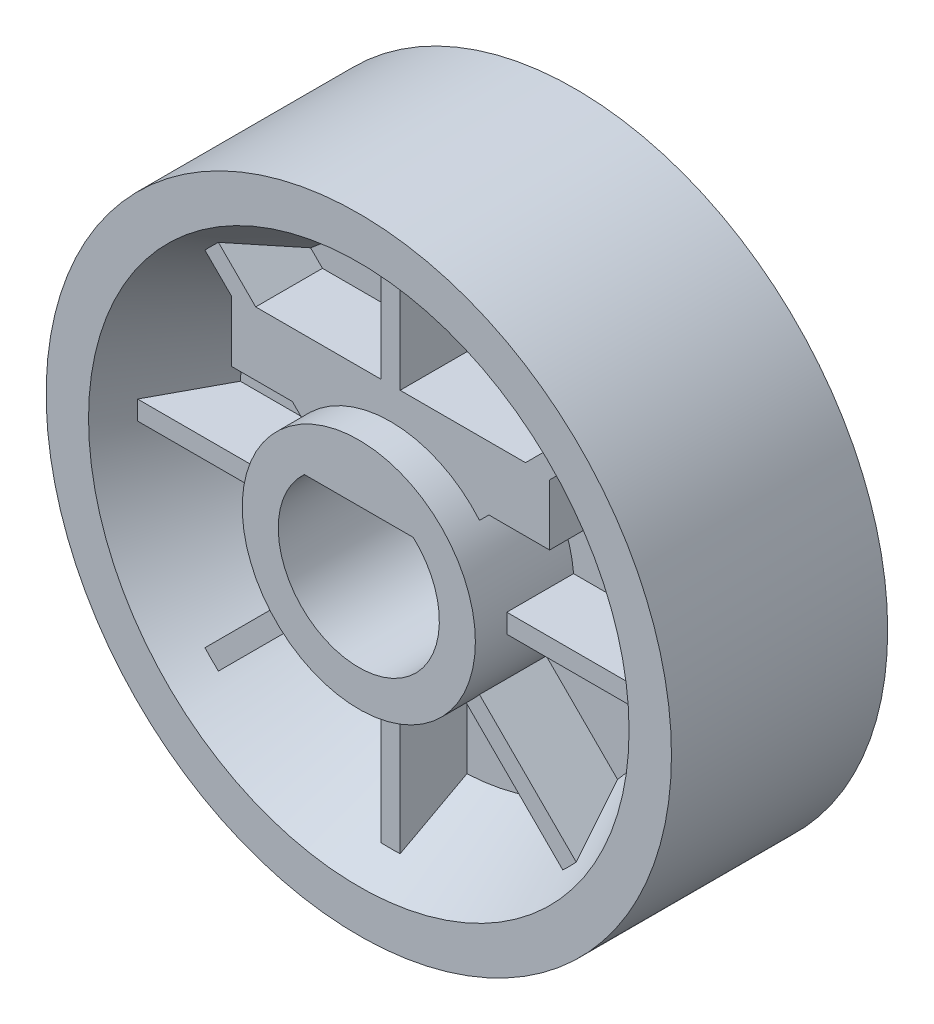
SolidWorks part; units mm, degrees
material "ABS"
ref_plane "Спереди" through (0, 0, 0) normal (0, 0, 1) x (1, 0, 0)
ref_plane "Сверху" through (0, 0, 0) normal (0, 1, 0) x (1, 0, 0)
ref_plane "Справа" through (0, 0, 0) normal (1, 0, 0) x (0, 0, -1)
sketch "Эскиз1" plane through (0, 0, 0) normal (0, 1, 0) x (1, 0, 0)
  line L0 (0, 0) -> (0, 15.044) construction
  line L1 (0, 0) -> (-5, 0) construction
  line L2 (-5, 0) -> (-11, 0)
  line L3 (-11, 0) -> (-11, 9.3)
  line L4 (-11, 9.3) -> (-20.5, 9.3)
  line L5 (-20.5, 9.3) -> (-25.5, 0)
  line L6 (-25.5, 0) -> (-29.5, 0)
  line L7 (-29.5, 0) -> (-29.5, 20.4)
  line L8 (-5, 0) -> (-5, 20.4)
  line L9 (-5, 10.2) -> (-29.5, 10.2) construction
  line L10 (-25.5, 20.4) -> (-29.5, 20.4)
  line L11 (-20.5, 11.1) -> (-25.5, 20.4)
  line L12 (-11, 11.1) -> (-20.5, 11.1)
  line L13 (-11, 20.4) -> (-11, 11.1)
  line L14 (-5, 20.4) -> (-11, 20.4)
  dimension "D1" = 10
  dimension "D2" = 22
  dimension "D3" = 41
  dimension "D4" = 59
  dimension "D5" = 51
  dimension "D6" = 10.2
  dimension "D7" = 9.3
revolve "Повернуть1" add sketch "Эскиз1" angle 360 about L0
sketch "Эскиз2" plane through (0, 0, 0) normal (0, 0, 1) x (1, 0, 0)
  line L0 (-5.1381, 5.6) -> (5.1381, 5.6)
  circle A0 centre (0, 0) radius 7.6
  circle M1 centre (0, 0) radius 5
  dimension "D1" = 15.2
  dimension "D2" = 13.2
extrude "Вырез-Вытянуть1" cut sketch "Эскиз2" against normal through all contours L0 A0 M1
ref_plane "Плоскость1" through (0, 0, -3) normal (0, 0, 1) x (1, 0, 0)
sketch "Эскиз3" plane through (0, 0, -3) normal (0, 0, 1) x (1, 0, 0)
  line L0 (0, 0) -> (0, 34) construction
  line L1 (5.0205, 6.2933) -> (6.2933, 5.0205)
  line L2 (-0.9, 8) -> (0.9, 8)
  line L3 (-0.9, 8) -> (-0.9, 26)
  line L4 (-0.9, 26) -> (0.9, 26)
  line L5 (0.9, 8) -> (0.9, 26)
  line L6 (-0.9, 8) -> (0.9, 26) construction
  line L7 (-0.9, 26) -> (0.9, 8) construction
  line L8 (5.0205, 6.2933) -> (17.7484, 19.0212)
  line L9 (17.7484, 19.0212) -> (19.0212, 17.7484)
  line L10 (6.2933, 5.0205) -> (19.0212, 17.7484)
  line L11 (5.0205, 6.2933) -> (19.0212, 17.7484) construction
  line L12 (17.7484, 19.0212) -> (6.2933, 5.0205) construction
  line L13 (8, 0.9) -> (8, -0.9)
  line L14 (8, 0.9) -> (26, 0.9)
  line L15 (26, 0.9) -> (26, -0.9)
  line L16 (8, -0.9) -> (26, -0.9)
  line L17 (8, 0.9) -> (26, -0.9) construction
  line L18 (26, 0.9) -> (8, -0.9) construction
  line L19 (6.2933, -5.0205) -> (5.0205, -6.2933)
  line L20 (6.2933, -5.0205) -> (19.0212, -17.7484)
  line L21 (19.0212, -17.7484) -> (17.7484, -19.0212)
  line L22 (5.0205, -6.2933) -> (17.7484, -19.0212)
  line L23 (6.2933, -5.0205) -> (17.7484, -19.0212) construction
  line L24 (19.0212, -17.7484) -> (5.0205, -6.2933) construction
  line L25 (0.9, -8) -> (-0.9, -8)
  line L26 (0.9, -8) -> (0.9, -26)
  line L27 (0.9, -26) -> (-0.9, -26)
  line L28 (-0.9, -8) -> (-0.9, -26)
  line L29 (0.9, -8) -> (-0.9, -26) construction
  line L30 (0.9, -26) -> (-0.9, -8) construction
  line L31 (-5.0205, -6.2933) -> (-6.2933, -5.0205)
  line L32 (-5.0205, -6.2933) -> (-17.7484, -19.0212)
  line L33 (-17.7484, -19.0212) -> (-19.0212, -17.7484)
  line L34 (-6.2933, -5.0205) -> (-19.0212, -17.7484)
  line L35 (-5.0205, -6.2933) -> (-19.0212, -17.7484) construction
  line L36 (-17.7484, -19.0212) -> (-6.2933, -5.0205) construction
  line L37 (-8, -0.9) -> (-8, 0.9)
  line L38 (-8, -0.9) -> (-26, -0.9)
  line L39 (-26, -0.9) -> (-26, 0.9)
  line L40 (-8, 0.9) -> (-26, 0.9)
  line L41 (-8, -0.9) -> (-26, 0.9) construction
  line L42 (-26, -0.9) -> (-8, 0.9) construction
  line L43 (-6.2933, 5.0205) -> (-5.0205, 6.2933)
  line L44 (-6.2933, 5.0205) -> (-19.0212, 17.7484)
  line L45 (-19.0212, 17.7484) -> (-17.7484, 19.0212)
  line L46 (-5.0205, 6.2933) -> (-17.7484, 19.0212)
  line L47 (-6.2933, 5.0205) -> (-17.7484, 19.0212) construction
  line L48 (-19.0212, 17.7484) -> (-5.0205, 6.2933) construction
  point P6 (0, 17)
  point P11 (12.0208, 12.0208)
  point P16 (17, 0)
  point P21 (12.0208, -12.0208)
  point P26 (0, -17)
  point P31 (-12.0208, -12.0208)
  point P36 (-17, 0)
  point P41 (-12.0208, 12.0208)
  point P46 (0, 0)
  dimension "D1" = 1.8
  dimension "D2" = 8
  dimension "D3" = 8
extrude "Бобышка-Вытянуть1" add sketch "Эскиз3" against normal blind 15
sketch "Эскиз4" plane through (0, 0, -3) normal (0, 0, 1) x (1, 0, 0)
  line L0 (0, 0) -> (0, 11) construction
  line L2 (15, 8) -> (-15, 8)
  line L3 (15, 8) -> (15, 14)
  line L4 (15, 14) -> (-15, 14)
  line L5 (-15, 8) -> (-15, 14)
  line L6 (15, 8) -> (-15, 14) construction
  line L7 (15, 14) -> (-15, 8) construction
  arc A0 (0.9, 10.9631) -> (-0.9, 10.9631) centre (0, 0) ccw construction
  dimension "D1" = 6
  dimension "D2" = 30
extrude "Бобышка-Вытянуть2" add sketch "Эскиз4" against normal blind 15
scale "Масштаб1" scale about centroid uniform scaling yes scale factor 1.01
